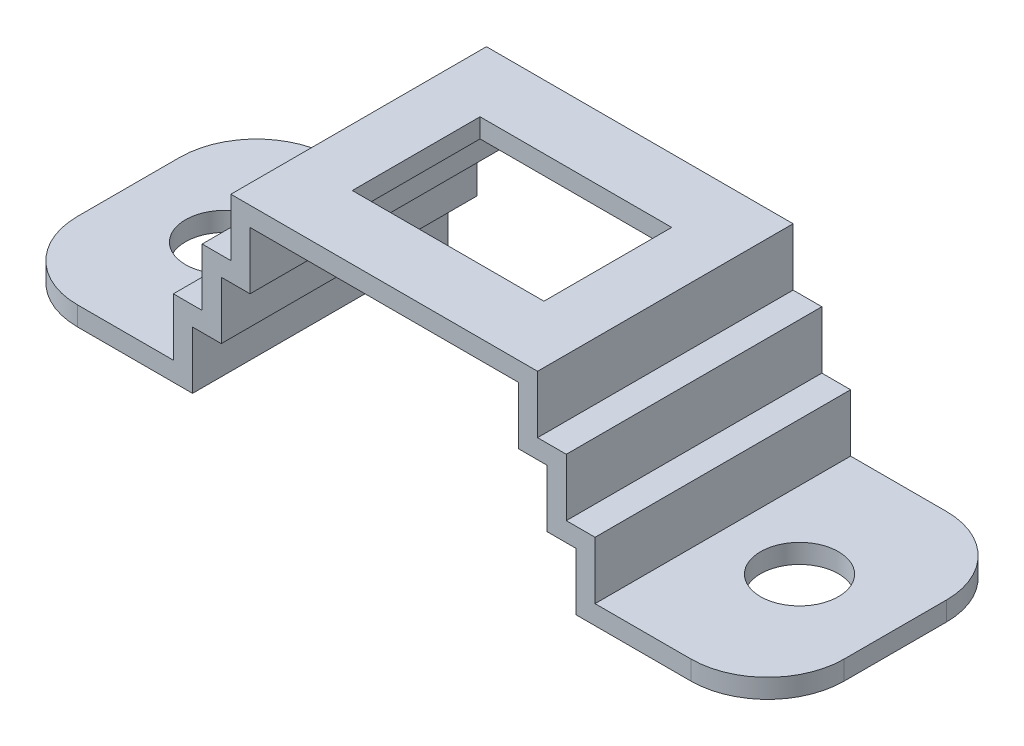
SolidWorks part; units mm, degrees
ref_plane "Front Plane" through (0, 0, 0) normal (0, 0, 1) x (1, 0, 0)
ref_plane "Top Plane" through (0, 0, 0) normal (0, 1, 0) x (1, 0, 0)
ref_plane "Right Plane" through (0, 0, 0) normal (1, 0, 0) x (0, 0, -1)
sketch "Sketch1" plane through (0, 0, 0) normal (0, 0, 1) x (1, 0, 0)
  line L0 (-60, 0) -> (-30, 0)
  line L1 (-30, 0) -> (-30, 9)
  line L2 (-30, 9) -> (-25.5, 9)
  line L3 (-25.5, 9) -> (-25.5, 18)
  line L4 (-25.5, 18) -> (-21, 18)
  line L5 (-21, 18) -> (-21, 27)
  line L6 (-21, 27) -> (0, 27)
  circle A0 centre (0, 0) radius 27.05
  dimension "D1" = 54.1
  dimension "D2" = 9
  dimension "D3" = 30
  dimension "D4" = 4.5
  dimension "D5" = 30
  dimension "D6" = 21
extrude "Extrude-Thin1" add sketch "Sketch1" against normal mid plane 40 thin contours L0 L1 L2 L3 L4 L5 L6
mirror "Mirror1" about plane through (0, 30, -20) normal (-1, 0, 0) of "Extrude-Thin1"
sketch "Sketch2" plane through (0, 30, 0) normal (0, 1, 0) x (1, 0, 0)
  line L1 (15, -10) -> (-15, -10)
  line L2 (15, -10) -> (15, 10)
  line L3 (15, 10) -> (-15, 10)
  line L4 (-15, -10) -> (-15, 10)
  line L5 (15, -10) -> (-15, 10) construction
  line L6 (15, 10) -> (-15, -10) construction
  point P0 (0, 0)
  dimension "D1" = 30
  dimension "D2" = 20
extrude "Cut-Extrude1" cut sketch "Sketch2" against normal through all
sketch "Sketch3" plane through (0, 3, 0) normal (0, 1, 0) x (1, 0, 0)
  line L1 (15, 10) -> (-15, 10) construction
  circle A0 centre (-45, 0) radius 6.1
  point P4 (0, 10)
  dimension "D1" = 12.2
  dimension "D2" = 45
extrude "Cut-Extrude2" cut sketch "Sketch3" against normal through all
mirror "Mirror2" about plane through (0, 0, 0) normal (1, 0, 0) of "Cut-Extrude2"
fillet "Fillet1" radius 12 4 edges at (-60, 1.5, 20) (-60, 1.5, -20) (60, 1.5, -20) (60, 1.5, 20)
